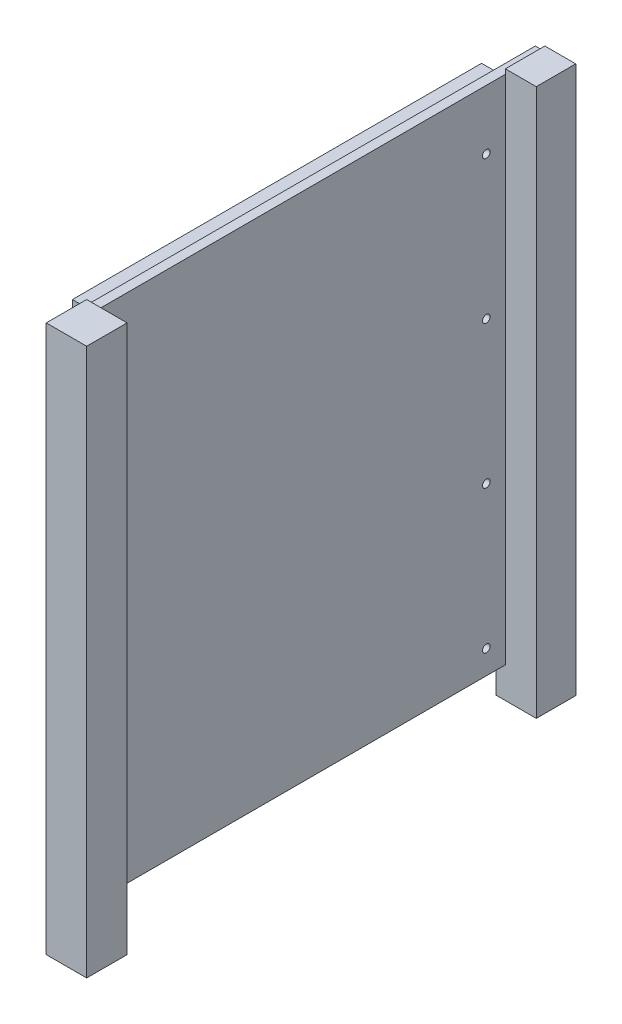
SolidWorks part; units mm, degrees
material "6061-T6 (SS)"
ref_plane "Front Plane" through (0, 0, 0) normal (0, 0, 1) x (1, 0, 0)
ref_plane "Top Plane" through (0, 0, 0) normal (0, 1, 0) x (1, 0, 0)
ref_plane "Right Plane" through (0, 0, 0) normal (1, 0, 0) x (0, 0, -1)
ref_plane "Plane1" through (4.25, 0, 0) normal (1, 0, 0) x (0, 0, -1)
sketch "Sketch1" plane through (4.25, 0, 0) normal (1, 0, 0) x (0, 0, -1)
  line L0 (-4.25, 0) -> (4.25, 0)
  line L1 (4.25, 0) -> (4.25, 115)
  line L2 (4.25, 115) -> (-4.25, 115)
  line L3 (-4.25, 115) -> (-4.25, 0)
  point P5 (0, 0)
  dimension "D1" = 115
  dimension "D2" = 8.5
  dimension "D3" = 4.25
extrude "Boss-Extrude1" add sketch "Sketch1" against normal blind 8.5
ref_plane "Plane2" through (-4.25, 0, 0) normal (-1, 0, 0) x (0, -1, 0)
sketch "Sketch2" plane through (-4.25, 0, 0) normal (-1, 0, 0) x (0, -1, 0)
  line L0 (-6.5, -90.25) -> (-6.5, -4.25)
  line L1 (-6.5, -4.25) -> (-114, -4.25)
  line L2 (0, -98.55) -> (-114, -98.55)
  line L3 (-114, -98.55) -> (-114, -4.25)
  line L4 (-115, 4.25) -> (0, 4.25) construction
  line L6 (0, -98.55) -> (0, -90.25)
  line L7 (0, -90.25) -> (-6.5, -90.25)
  dimension "D1" = 114
  dimension "D2" = 6.5
  dimension "D3" = 86
  dimension "D4" = 8.3
  dimension "D5" = 6.5
  dimension "D6" = 8.5
extrude "Boss-Extrude2" add sketch "Sketch2" against normal blind 2
sketch "Sketch3" plane through (-2.25, 0, 0) normal (1, 0, 0) x (0, 0, -1)
  line L0 (90.25, 0) -> (90.25, 115)
  line L1 (90.25, 115) -> (98.55, 115)
  line L2 (98.55, 115) -> (98.55, 0)
  line L3 (98.55, 0) -> (90.25, 0)
  line L4 (90.25, 6.5) -> (4.25, 6.5) construction
  dimension "D1" = 115
  dimension "D2" = 8.3
  dimension "D3" = 86
  dimension "D4" = 6.5
extrude "Boss-Extrude3" add sketch "Sketch3" along normal blind 6.5
ref_plane "Z_midplane" through (0, 57.5, 0) normal (0, 1, 0) x (1, 0, 0)
sketch "Sketch4" plane through (-4.25, 0, 0) normal (-1, 0, 0) x (0, 0, 1)
  line L0 (-4.25, 6.5) -> (-90.25, 6.5)
  line L1 (-90.25, 6.5) -> (-90.25, 113.5)
  line L2 (-90.25, 113.5) -> (-4.25, 113.5)
  line L3 (-4.25, 113.5) -> (-4.25, 6.5)
  line L4 (-4.25, 0) -> (-4.25, 115) construction
  line L6 (-90.25, 6.5) -> (-90.25, 114) construction
  line L8 (4.25, 0) -> (-4.25, 0) construction
  dimension "D1" = 107
  dimension "D2" = 0
  dimension "D3" = 0
  dimension "D4" = 6.5
extrude "Boss-Extrude4" add sketch "Sketch4" along normal blind 3
sketch "Sketch5" plane through (-2.25, 0, 0) normal (1, 0, 0) x (0, 0, -1)
  line L0 (8.25, 10.5) -> (86.25, 10.5)
  line L1 (86.25, 10.5) -> (86.25, 109.5)
  line L2 (86.25, 109.5) -> (8.25, 109.5)
  line L3 (8.25, 109.5) -> (8.25, 10.5)
  line L4 (90.25, 6.5) -> (4.25, 6.5) construction
  line L5 (4.25, 6.5) -> (4.25, 113.5) construction
  line L6 (90.25, 113.5) -> (90.25, 6.5) construction
  line L7 (4.25, 113.5) -> (90.25, 113.5) construction
  dimension "D1" = 4
  dimension "D2" = 4
  dimension "D3" = 4
  dimension "D4" = 4
extrude "Cut-Extrude1" cut sketch "Sketch5" against normal through all
fillet "Fillet2" radius 3 4 edges at (-4.75, 10.5, -8.25) (-4.75, 109.5, -86.25) (-4.75, 109.5, -8.25) (-4.75, 10.5, -86.25)
fillet "Fillet12" radius 2 1 edges at (-5.75, 6.5, -90.25)
fillet "Fillet13" radius 2 2 edges
ref_plane "Y_midplane" through (0, 0, -47.25) normal (0, 0, 1) x (1, 0, 0)
ref_plane "Plane13" [suppressed] through (0, 104.4, 0) normal (0, 1, 0) x (1, 0, 0)
ref_plane "center_Y" through (0, 0, -47.25) normal (0, 0, 1) x (1, 0, 0)
ref_plane "center_Z" through (0, 60, 0) normal (0, 1, 0) x (1, 0, 0)
sketch "Sketch58" plane through (-2.25, 0, 0) normal (1, 0, 0) x (0, 0, -1)
  line L0 (11.25, 10.5) -> (83.25, 10.5) construction
  line L1 (44.75, 10.5) -> (49.75, 10.5)
  line L2 (44.75, 10.5) -> (44.75, 12)
  line L3 (44.75, 12) -> (49.75, 12)
  line L4 (49.75, 10.5) -> (49.75, 12)
  line L5 (90.25, 6.5) -> (4.25, 6.5) construction
  point P6 (47.25, 6.5)
  point P11 (47.25, 10.5)
  dimension "D1" = 5
  dimension "D2" = 5.5
sketch "Sketch62" plane through (-4.25, 0, 0) normal (-1, 0, 0) x (0, 0, 1)
  line L0 (-47.25, 113.5) -> (-47.25, 6.2288) construction
  line L1 (-4.25, 113.5) -> (-90.25, 113.5) construction
  line L2 (-98.55, 57) -> (4.25, 57.5) construction
  line L3 (4.25, 115) -> (4.25, 0) construction
  line L4 (-98.55, 114) -> (-98.55, 0) construction
  line L5 (-4.25, 115) -> (4.25, 115) construction
  circle A0 centre (0, 108) radius 1
  circle A1 centre (-94.5, 108) radius 1
  circle A2 centre (-94.0041, 6.0418) radius 1
  circle A3 centre (0.4914, 6.961) radius 1
  dimension "D1" = 2
  dimension "D2" = 4.25
  dimension "D3" = 7
sketch "Sketch64" plane through (-2.25, 0, 0) normal (1, 0, 0) x (0, 0, -1)
  line L0 (86.25, 13.5) -> (86.25, 106.5) construction
  line L1 (86.25, 109.5) -> (8.25, 109.5)
  line L2 (86.25, 109.5) -> (86.25, 10.5)
  line L3 (86.25, 10.5) -> (8.25, 10.5)
  line L4 (8.25, 109.5) -> (8.25, 10.5)
  line L5 (83.25, 109.5) -> (11.25, 109.5) construction
  line L6 (11.25, 10.5) -> (83.25, 10.5) construction
  line L7 (8.25, 106.5) -> (8.25, 13.5) construction
  dimension "D1" = 0
  dimension "D2" = 0
  dimension "D3" = 0
  dimension "D4" = 0
extrude "Boss-Extrude12" add sketch "Sketch64" against normal up to surface (5 mm away) up to face at (-7.25, 60, -47.25)
hole_wizard "M2x0.4 Tapped Hole1" positions "Sketch27" profile "Sketch26" tap size "M2x0.4" standard "ANSI Metric" end condition through all
sketch "Sketch27" plane through (-7.25, 0, 0) normal (-1, 0, 0) x (0, 0, 1)
  line L0 (-88.25, 6.5) -> (-6.25, 6.5) construction
  line L13 (-47.25, 113.5) -> (-47.25, 6.5) construction
  line L15 (-90.25, 115) -> (-90.25, 0) construction
  line L18 (-90.25, 6.5) -> (-4.25, 6.5) construction
  point P0 (-8.25, 11.5)
  point P31 (-8.25, 41.5)
  point P32 (-8.25, 71.5)
  point P33 (-8.25, 101.5)
  point P100 (0, 0)
  point P105 (-47.25, 103.3415)
  point P110 (-8.25, 71.5)
  point P115 (-88.25, 11.5)
  point P116 (0, 0)
  point P117 (-86.25, 11.5)
  point P118 (-86.25, 41.5)
  point P119 (-86.25, 71.5)
  point P120 (-86.25, 101.5)
  dimension "D1" = 5
  dimension "D4" = 30
  dimension "D5" = 43
  dimension "D7" = 107
  dimension "D10" = 0
  dimension "D11" = 39
  dimension "D3" = 4
sketch "Sketch26" plane through (-7.25, 11.5, -8.25) normal (0, 1, 0) x (0, 0, 1)
  line L0 (0, 0) -> (0, 11.5)
  line L1 (0, 11.5) -> (0.8, 11.5)
  line L2 (0.8, 11.5) -> (0.8, 0)
  line L5 (0.8, 0) -> (0, 0)
  line L11 (0, -6.35) -> (0, 107.95) construction
  dimension "Thru Tap Drill Dia." = 1.6
  dimension "Thru Tap Drill Depth" = 11.5
cosmetic thread "Hole Thread51" parameters "D2"=2
cosmetic thread "Hole Thread52" parameters "D2"=2
cosmetic thread "Hole Thread53" parameters "D2"=2
cosmetic thread "Hole Thread54" parameters "D2"=2
cosmetic thread "Hole Thread62" parameters "D2"=2
cosmetic thread "Hole Thread63" parameters "D2"=2
cosmetic thread "Hole Thread64" parameters "D2"=2
cosmetic thread "Hole Thread65" parameters "D2"=2
equation "\"D2@Sketch56\"=\"D1@Sketch56\""
equation "\"D3@Sketch48\"=\"D2@Sketch48\""
